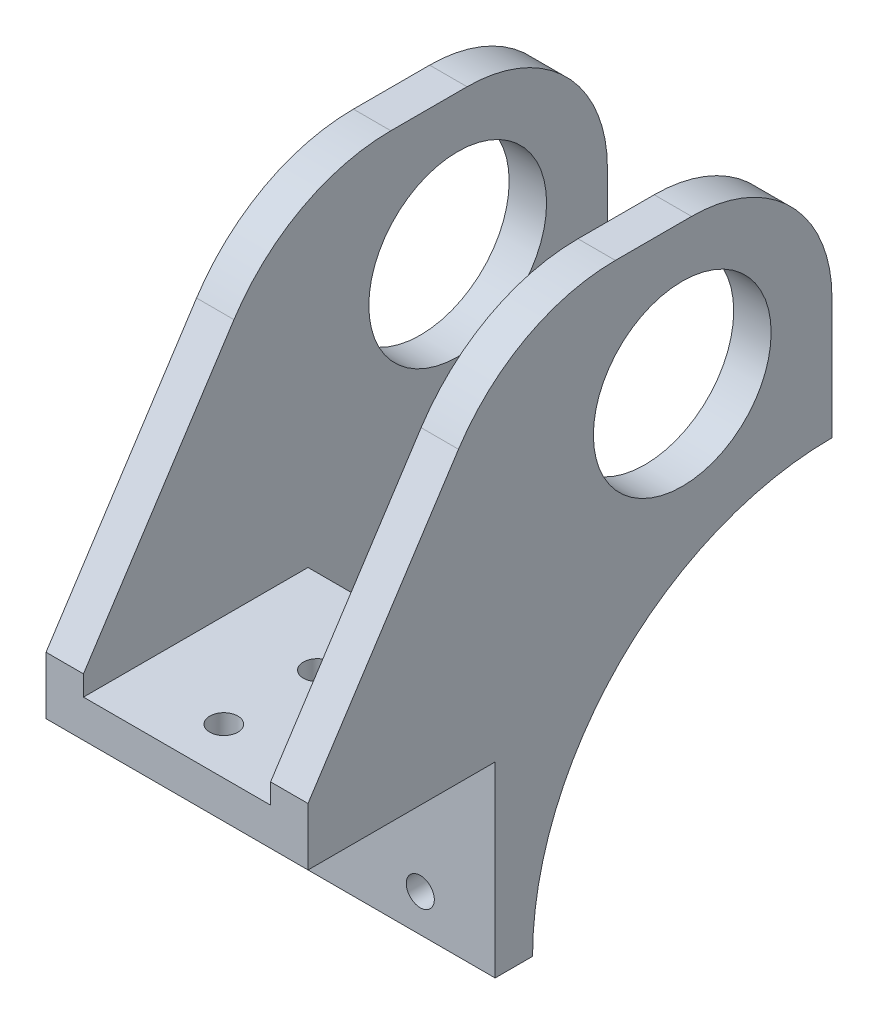
SolidWorks part; units mm, degrees
material "1060 合金"
ref_plane "前视基准面" through (0, 0, 0) normal (0, 0, 1) x (1, 0, 0)
ref_plane "上视基准面" through (0, 0, 0) normal (0, 1, 0) x (1, 0, 0)
ref_plane "右视基准面" through (0, 0, 0) normal (1, 0, 0) x (0, 0, -1)
sketch "草图1" plane through (0, 0, 0) normal (0, 0, 1) x (1, 0, 0)
  line L5 (30, -4) -> (30, 38)
  line L6 (30, 38) -> (34, 38)
  line L7 (34, 38) -> (34, 0)
  line L8 (34, 0) -> (46, 0)
  line L9 (46, 0) -> (46, 38)
  line L10 (46, 38) -> (50, 38)
  line L11 (50, 38) -> (50, -4)
  line L12 (50, -4) -> (30, -4)
  dimension "D1" = 4
  dimension "D2" = 4
  dimension "D3" = 42
  dimension "D6" = 12
  dimension "D7" = 4
extrude "凸台-拉伸1" add sketch "草图1" along normal mid plane 80
sketch "草图2" plane through (50, 0, 0) normal (1, 0, 0) x (0, 0, -1)
  line L0 (0, 38) -> (0, -4) construction
  line L1 (-40, 38) -> (40, 38) construction
  line L2 (-40, -4) -> (40, -4) construction
  circle A0 centre (22, 22) radius 9.5
  circle A1 centre (-22, 22) radius 9.5
  dimension "D1" = 19
  dimension "D2" = 16
  dimension "D3" = 22
extrude "切除-拉伸1" cut sketch "草图2" against normal through all
fillet "圆角1" radius 10 4 edges at (32, 38, 40) (48, 38, 40) (32, 38, -40) (48, 38, -40)
sketch "草图5" plane through (50, 0, 0) normal (1, 0, 0) x (0, 0, -1)
  line L0 (22, 22) -> (22, 37) construction
  line L1 (22, 22) -> (34.9904, 29.5) construction
  line L2 (0, -4) -> (0, 38) construction
  line L3 (-40, -4) -> (40, -4) construction
  line L4 (-30, 38) -> (30, 38) construction
  circle A0 centre (22, 22) radius 15 construction
  circle A2 centre (34.9904, 29.5) radius 1.5
  circle A3 centre (22, 7) radius 1.5
  circle A4 centre (9.0096, 29.5) radius 1.5
  circle A5 centre (-34.9904, 29.5) radius 1.5
  circle A6 centre (-22, 7) radius 1.5
  circle A7 centre (-9.0096, 29.5) radius 1.5
  point P12 (22, 22)
  dimension "D1" = 30
  dimension "D3" = 3
  dimension "D2" = 60
  dimension "D4" = 3
extrude "切除-拉伸4" cut sketch "草图5" against normal through all
sketch "草图6" plane through (30, 0, 0) normal (-1, 0, 0) x (0, 0, 1)
  circle A0 centre (-22, 22) radius 9.5 construction
  circle A1 centre (-22, 22) radius 9.5
  circle A2 centre (22, 22) radius 9.5 construction
  circle A3 centre (22, 22) radius 9.5
  circle A4 centre (-22, 22) radius 10.5
  circle A5 centre (22, 22) radius 10.5
  dimension "D1" = 1
extrude "切除-拉伸5" cut sketch "草图6" against normal blind 1.5
sketch "草图7" plane through (50, 0, 0) normal (1, 0, 0) x (0, 0, -1)
  line L0 (40, 28) -> (9.0096, 28) construction
  line L1 (9.0096, 28) -> (3.9996, 28) construction
  line L2 (3.9996, 28) -> (3.9996, 38) construction
  line L3 (-30, 38) -> (30, 38) construction
  line L5 (3.9996, 38) -> (-47.4626, 38)
  line L6 (3.9996, 38) -> (3.9996, -10.1754)
  line L7 (3.9996, -10.1754) -> (-47.4626, -10.1754)
  line L8 (-47.4626, 38) -> (-47.4626, -10.1754)
  circle A0 centre (9.0096, 29.5) radius 1.5 construction
  dimension "D1" = 48.1754
  dimension "D2" = 51.4622
extrude "切除-拉伸6" cut sketch "草图7" against normal blind 47
fillet "圆角2" radius 10 2 edges at (32, 38, -3.9996) (48, 38, -3.9996)
sketch "草图11" plane through (31.5, 0, 0) normal (-1, 0, 0) x (0, 0, 1)
  circle A1 centre (-22, 22) radius 11.25
  circle A2 centre (-22, 22) radius 11.5
  circle M3 centre (-22, 22) radius 10.5
extrude "凸台-拉伸3" add sketch "草图11" along normal blind 1.5 contours A1 M3
sketch "草图12" plane through (31.5, 0, 0) normal (-1, 0, 0) x (0, 0, 1)
  circle A0 centre (-22, 22) radius 10.5
  circle A1 centre (-22, 22) radius 11.25
extrude "凸台-拉伸4" add sketch "草图12" along normal blind 0.7
sketch "草图13" plane through (50, 0, 0) normal (1, 0, 0) x (0, 0, -1)
  circle A0 centre (22, 22) radius 10.5
  circle A1 centre (22, 22) radius 9.5
extrude "切除-拉伸8" cut sketch "草图13" against normal blind 1
sketch "草图15" plane through (31.5, 0, 0) normal (-1, 0, 0) x (0, 0, 1)
  circle A0 centre (-22, 22) radius 9.5
  circle A1 centre (-22, 22) radius 10.5
extrude "凸台-拉伸5" add sketch "草图15" along normal blind 0.5
sketch "草图17" plane through (0, 0, 0) normal (0, 1, 0) x (1, 0, 0)
  line L4 (34, 40) -> (34, 3.9996)
  line L5 (34, 3.9996) -> (46, 3.9996)
  line L6 (46, 3.9996) -> (46, 40)
  line L7 (46, 40) -> (34, 40)
  line L8 (34, 40) -> (34, 3.9996)
  line L10 (46, 3.9996) -> (46, 40)
  line L11 (46, 40) -> (34, 40)
  line L15 (34, 3.9996) -> (46, 3.9996)
  dimension "D1" = 0
extrude "凸台-拉伸6" add sketch "草图17" along normal blind 2
sketch "草图18" plane through (0, -4, 0) normal (0, -1, 0) x (1, 0, 0)
  line L4 (50, -40) -> (50, -3.9996)
  line L5 (50, -3.9996) -> (30, -3.9996)
  line L6 (30, -3.9996) -> (30, -40)
  line L7 (30, -40) -> (50, -40)
  line L8 (50, -40) -> (50, -3.9996)
  line L10 (30, -3.9996) -> (30, -40)
  line L11 (30, -40) -> (50, -40)
  line L15 (50, -3.9996) -> (30, -3.9996)
  dimension "D1" = 0
extrude "切除-拉伸9" cut sketch "草图18" against normal blind 2
sketch "草图19" plane through (50, 0, 0) normal (1, 0, 0) x (0, 0, -1)
  circle A0 centre (34.9904, 29.5) radius 1.5
  circle A1 centre (9.0096, 29.5) radius 1.5
  circle A2 centre (22, 7) radius 1.5
extrude "凸台-拉伸7" add sketch "草图19" against normal blind 4
sketch "草图20" plane through (30, 0, 0) normal (-1, 0, 0) x (0, 0, 1)
  circle A0 centre (-9.0096, 29.5) radius 1.5
  circle A1 centre (-22, 7) radius 1.5
  circle A2 centre (-34.9904, 29.5) radius 1.5
extrude "凸台-拉伸8" add sketch "草图20" against normal blind 4
sketch "草图21" plane through (30, 0, 0) normal (-1, 0, 0) x (0, 0, 1)
  line L1 (-3.9996, -2) -> (-40, -2) construction
  line L4 (-7.9998, -2) -> (-7.9998, 38)
  line L6 (-35.9998, -2) -> (-35.9998, 38)
  line L7 (-7.9998, 38) -> (-3.9996, 38)
  line L8 (-7.9998, 38) -> (-7.9998, -2)
  line L9 (-7.9998, -2) -> (-3.9996, -2)
  line L10 (-3.9996, 38) -> (-3.9996, -2)
  line L11 (-40, -2) -> (-35.9998, -2)
  line L12 (-40, -2) -> (-40, 38)
  line L13 (-40, 38) -> (-35.9998, 38)
  line L14 (-35.9998, -2) -> (-35.9998, 38)
  line M3 (-40, -2) -> (-3.9996, -2)
  line M4 (-3.9996, -2) -> (-3.9996, 28)
  arc M5 (-3.9996, 28) -> (-13.9996, 38) centre (-13.9996, 28) ccw
  arc M7 (-30, 38) -> (-40, 28) centre (-30, 28) ccw
  line M8 (-40, 28) -> (-40, -2)
  dimension "D1" = 40
  dimension "D2" = 28
  dimension "D3" = 40
  dimension "D4" = 4.0002
  dimension "D5" = 40
  dimension "D6" = 4.0002
extrude "凸台-拉伸9" add sketch "草图21" against normal blind 44 contours L6 M3 M7 M8 | L4 M3 M4 M5
sketch "草图22" plane through (50, 0, 0) normal (1, 0, 0) x (0, 0, -1)
  line L1 (-4.3042, -4.252) -> (60.1949, -4.252)
  line L2 (-4.3042, -4.252) -> (-4.3042, 45.5118)
  line L3 (-4.3042, 45.5118) -> (60.1949, 45.5118)
  line L4 (60.1949, -4.252) -> (60.1949, 45.5118)
  dimension "D1" = 49.7638
  dimension "D2" = 64.499
extrude "切除-拉伸10" cut sketch "草图22" along normal blind 38
sketch "草图23" plane through (0, 0, -3.9996) normal (0, 0, 1) x (1, 0, 0)
  line L0 (50, -2) -> (46, -2) construction
  line L1 (50, -2) -> (30, -2) construction
  line L2 (46, -2) -> (46, 2) construction
  line L4 (46, 2) -> (34, 2)
  line L5 (46, 2) -> (46, 36.0001)
  line L6 (46, 36.0001) -> (34, 36.0001)
  line L7 (34, 2) -> (34, 36.0001)
  dimension "D1" = 34.0001
  dimension "D2" = 12
extrude "切除-拉伸12" cut sketch "草图23" against normal blind 38
sketch "草图24" plane through (0, 0, -3.9996) normal (0, 0, 1) x (1, 0, 0)
  line L1 (30, -2) -> (53.9454, -2)
  line L2 (30, -2) -> (30, 46.4262)
  line L3 (30, 46.4262) -> (53.9454, 46.4262)
  line L4 (53.9454, -2) -> (53.9454, 46.4262)
  dimension "D1" = 48.4262
  dimension "D2" = 23.9454
extrude "切除-拉伸13" cut sketch "草图24" against normal blind 4
sketch "草图25" plane through (0, 0, -40) normal (0, 0, -1) x (-1, 0, 0)
  line L1 (-50, -2) -> (-30, -2)
  line L2 (-50, -2) -> (-50, 38)
  line L3 (-50, 38) -> (-30, 38)
  line L4 (-30, -2) -> (-30, 38)
  dimension "D1" = 40
  dimension "D2" = 20
extrude "切除-拉伸14" cut sketch "草图25" against normal blind 4
sketch "草图26" plane through (50, 0, 0) normal (1, 0, 0) x (0, 0, -1)
  line L1 (13.9996, 38) -> (7.9996, 38)
  line L4 (7.9996, 38) -> (7.9996, 36)
  line L5 (30, 38) -> (36, 38)
  line L8 (36, 38) -> (36, 36)
  arc A0 (36, 36) -> (30, 38) centre (30, 28) ccw
  arc A1 (13.9996, 38) -> (7.9996, 36) centre (13.9996, 28) ccw
  dimension "D2" = 6
  dimension "D4" = 6
extrude "凸台-拉伸10" add sketch "草图26" against normal blind 4
sketch "草图27" plane through (30, 0, 0) normal (-1, 0, 0) x (0, 0, 1)
  line L1 (-7.9996, 38) -> (-13.9996, 38)
  line L2 (-7.9996, 38) -> (-7.9996, 36)
  line L5 (-36, 38) -> (-30, 38)
  line L6 (-36, 38) -> (-36, 36)
  arc A0 (-7.9996, 36) -> (-13.9996, 38) centre (-13.9996, 28) ccw
  arc A1 (-30, 38) -> (-36, 36) centre (-30, 28) ccw
extrude "凸台-拉伸11" add sketch "草图27" against normal blind 4
sketch "草图30" plane through (50, 0, 0) normal (1, 0, 0) x (0, 0, -1)
  circle A0 centre (22, 22) radius 7.5
  circle A1 centre (22, 22) radius 10.5
extrude "凸台-拉伸12" add sketch "草图30" against normal blind 4
sketch "草图31" plane through (31, 0, 0) normal (-1, 0, 0) x (0, 0, 1)
  circle A1 centre (-22, 22) radius 9.5
  circle A2 centre (-22, 22) radius 10.5
extrude "凸台-拉伸13" add sketch "草图31" along normal blind 1
sketch "草图32" plane through (50, 0, 0) normal (1, 0, 0) x (0, 0, -1)
  circle A0 centre (22, 22) radius 7.5
  circle A1 centre (22, 22) radius 8.25
extrude "切除-拉伸15" cut sketch "草图32" against normal blind 0.8
sketch "草图34" plane through (0, -2, 0) normal (0, -1, 0) x (1, 0, 0)
  line L1 (30, -7.9996) -> (50, -7.9996)
  line L2 (30, -7.9996) -> (30, -11.9996)
  line L3 (30, -11.9996) -> (50, -11.9996)
  line L4 (50, -7.9996) -> (50, -11.9996)
  line L5 (50, -36) -> (50, -7.9996) construction
  line L7 (30, -36) -> (50, -36)
  line L8 (30, -36) -> (30, -32)
  line L9 (30, -32) -> (50, -32)
  line L10 (50, -36) -> (50, -32)
  dimension "D1" = 4
  dimension "D2" = 20
  dimension "D3" = 4
  dimension "D4" = 20
extrude "凸台-拉伸14" add sketch "草图34" along normal blind 20
sketch "草图37" plane through (50, 0, 0) normal (1, 0, 0) x (0, 0, -1)
  circle A0 centre (22, 22) radius 9.5
extrude "切除-拉伸19" cut sketch "草图37" against normal blind 10
sketch "草图38" plane through (50, 0, 0) normal (1, 0, 0) x (0, 0, -1)
  circle A0 centre (22, 22) radius 10.5
extrude "切除-拉伸20" cut sketch "草图38" against normal blind 1
sketch "草图39" plane through (0, 0, -36) normal (0, 0, -1) x (-1, 0, 0)
  line L0 (-30, -22) -> (-30, 38) construction
  line L1 (-50, 38) -> (-46, 38)
  line L2 (-50, 38) -> (-50, 2)
  line L3 (-50, 2) -> (-46, 2)
  line L4 (-46, 38) -> (-46, 2)
  line L5 (-34, 38) -> (-30, 38)
  line L6 (-34, 38) -> (-34, 2)
  line L7 (-34, 2) -> (-30, 2)
  line L8 (-30, 38) -> (-30, 2)
extrude "凸台-拉伸15" add sketch "草图39" along normal blind 22
sketch "草图40" plane through (30, 0, 0) normal (-1, 0, 0) x (0, 0, 1)
  line L0 (-22, 22) -> (-44, 22) construction
  circle A0 centre (-44, 22) radius 9.5
  dimension "D2" = 19
  dimension "D1" = 22
extrude "切除-拉伸21" cut sketch "草图40" against normal blind 22
sketch "草图41" plane through (30, 0, 0) normal (-1, 0, 0) x (0, 0, 1)
  circle A0 centre (-22, 22) radius 9.5
extrude "凸台-拉伸16" add sketch "草图41" against normal blind 4
sketch "草图44" plane through (50, 0, 0) normal (1, 0, 0) x (0, 0, -1)
  circle A0 centre (22, 22) radius 10.5
extrude "凸台-拉伸17" add sketch "草图44" against normal blind 4
sketch "草图45" plane through (30, 0, 0) normal (-1, 0, 0) x (0, 0, 1)
  line L10 (-7.9996, 38) -> (-58, 38)
  line L11 (-58, 38) -> (-58, 2)
  line L12 (-58, 2) -> (-36, 2)
  line L13 (-36, 2) -> (-36, -22)
  line L14 (-36, -22) -> (-32, -22)
  line L15 (-32, -22) -> (-32, -2)
  line L16 (-32, -2) -> (-11.9996, -2)
  line L17 (-11.9996, -2) -> (-11.9996, -22)
  line L18 (-11.9996, -22) -> (-7.9996, -22)
  line L19 (-7.9996, -22) -> (-7.9996, 38)
  line L20 (-7.9996, 38) -> (-58, 38)
  line L21 (-58, 38) -> (-58, 2)
  line L22 (-58, 2) -> (-36, 2)
  line L23 (-36, 2) -> (-36, -22)
  line L24 (-36, -22) -> (-32, -22)
  line L25 (-32, -22) -> (-32, -2)
  line L26 (-32, -2) -> (-11.9996, -2)
  line L27 (-11.9996, -2) -> (-11.9996, -22)
  line L28 (-11.9996, -22) -> (-7.9996, -22)
  line L29 (-7.9996, -22) -> (-7.9996, 38)
  circle A0 centre (-44, 22) radius 9.5
  dimension "D1" = 0
extrude "凸台-拉伸18" add sketch "草图45" along normal blind 8
sketch "草图46" plane through (34, 0, 0) normal (1, 0, 0) x (0, 0, -1)
  line L5 (7.9996, 2) -> (36, 2)
  line L6 (36, 2) -> (58, 2)
  line L7 (58, 2) -> (58, 38)
  line L8 (58, 38) -> (7.9996, 38)
  line L9 (7.9996, 38) -> (7.9996, 2)
  line L10 (7.9996, 2) -> (36, 2)
  line L11 (36, 2) -> (58, 2)
  line L12 (58, 2) -> (58, 38)
  line L13 (58, 38) -> (7.9996, 38)
  line L14 (7.9996, 38) -> (7.9996, 2)
  dimension "D1" = 0
extrude "切除-拉伸22" cut sketch "草图46" against normal blind 8
sketch "草图50" plane through (0, 0, -58) normal (0, 0, -1) x (-1, 0, 0)
  line L4 (-50, 38) -> (-50, 2)
  line L5 (-50, 2) -> (-46, 2)
  line L6 (-46, 2) -> (-46, 38)
  line L7 (-46, 38) -> (-50, 38)
  line L8 (-50, 38) -> (-50, 2)
  line L9 (-50, 2) -> (-46, 2)
  line L10 (-46, 2) -> (-46, 38)
  line L11 (-46, 38) -> (-50, 38)
  line L12 (-22, 38) -> (-26, 38)
  line L13 (-26, 38) -> (-26, 2)
  line L14 (-26, 2) -> (-22, 2)
  line L15 (-22, 2) -> (-22, 38)
  line L16 (-22, 38) -> (-26, 38)
  line L17 (-26, 38) -> (-26, 2)
  line L18 (-26, 2) -> (-22, 2)
  line L19 (-22, 2) -> (-22, 38)
  dimension "D1" = 0
  dimension "D2" = 0
extrude "凸台-拉伸19" add sketch "草图50" along normal blind 2
sketch "草图51" plane through (22, 0, 0) normal (-1, 0, 0) x (0, 0, 1)
  line L0 (-60, 2) -> (-36, 2)
  line L1 (-36, 2) -> (-36, -22) construction
  line L2 (-36, 2) -> (-36, -22)
  arc A1 (-36, -22) -> (-60, 2) centre (-60, -22) ccw
extrude "凸台-拉伸20" add sketch "草图51" against normal blind 4
sketch "草图54" plane through (50, 0, 0) normal (1, 0, 0) x (0, 0, -1)
  line L0 (36, 2) -> (36, -22) construction
  line L1 (60, 2) -> (36, 2) construction
  line L2 (36, 2) -> (36, -22)
  line L3 (60, 2) -> (36, 2)
  arc A0 (60, 2) -> (36, -22) centre (60, -22) ccw construction
  arc A1 (60, 2) -> (36, -22) centre (60, -22) ccw
extrude "凸台-拉伸21" add sketch "草图54" against normal blind 4
sketch "草图55" plane through (0, 0, -7.9996) normal (0, 0, 1) x (1, 0, 0)
  line L0 (36, -22) -> (36, -12) construction
  line L1 (50, -22) -> (22, -22) construction
  line L3 (30, -18) -> (42, -18) construction
  line L4 (30, -18) -> (30, -6) construction
  line L5 (30, -6) -> (42, -6) construction
  line L6 (42, -18) -> (42, -6) construction
  line L7 (30, -18) -> (42, -6) construction
  line L8 (30, -6) -> (42, -18) construction
  circle A0 centre (30, -6) radius 1.5
  circle A1 centre (42, -6) radius 1.5
  circle A2 centre (42, -18) radius 1.5
  circle A3 centre (30, -18) radius 1.5
  point P18 (36, -12)
  dimension "D3" = 3
  dimension "D1" = 10
  dimension "D2" = 12
  dimension "D4" = 4
extrude "切除-拉伸23" cut sketch "草图55" against normal blind 30
sketch "草图57" plane through (22, 0, 0) normal (-1, 0, 0) x (0, 0, 1)
  line L0 (-11.9996, -2) -> (-7.9996, -2) construction
  line L1 (-7.9996, -22) -> (-7.9996, 38) construction
  line L2 (-7.9996, -2) -> (-33.9998, 38)
  line L3 (-7.9996, 38) -> (-60, 38) construction
  line L4 (-33.9998, 38) -> (-7.9996, 38)
  line L5 (-7.9996, 38) -> (-7.9996, -2)
extrude "切除-拉伸24" cut sketch "草图57" against normal blind 30
fillet "圆角4" radius 20 2 edges at (24, 38, -33.9998) (48, 38, -33.9998)
sketch "草图58" plane through (0, 0, -11.9996) normal (0, 0, -1) x (-1, 0, 0)
  line L4 (-22, -2) -> (-50, -2)
  line L5 (-50, -2) -> (-50, -22)
  line L6 (-50, -22) -> (-22, -22)
  line L7 (-22, -22) -> (-22, -2)
  line L8 (-22, -2) -> (-50, -2)
  line L9 (-50, -2) -> (-50, -22)
  line L10 (-50, -22) -> (-22, -22)
  line L11 (-22, -22) -> (-22, -2)
  dimension "D1" = 0
extrude "切除-拉伸25" cut sketch "草图58" against normal blind 10
sketch "草图59" plane through (0, -2, 0) normal (0, -1, 0) x (1, 0, 0)
  line L0 (50, -32) -> (50, -7.9996) construction
  line L1 (22, -7.9996) -> (50, -7.9996)
  line L2 (22, -7.9996) -> (22, -11.9996)
  line L3 (22, -11.9996) -> (50, -11.9996)
  line L4 (50, -7.9996) -> (50, -11.9996)
  dimension "D1" = 4
extrude "切除-拉伸26" cut sketch "草图59" against normal blind 10
sketch "草图60" plane through (0, -2, 0) normal (0, -1, 0) x (1, 0, 0)
  line L0 (36, -11.9996) -> (36, -16.9996) construction
  line L1 (22, -11.9996) -> (50, -11.9996) construction
  line L2 (36, -16.9996) -> (36, -26.9996) construction
  circle A0 centre (36, -16.9996) radius 1.5
  circle A1 centre (36, -26.9996) radius 1.5
  dimension "D3" = 3
  dimension "D4" = 3
  dimension "D1" = 5
  dimension "D2" = 10
extrude "切除-拉伸27" cut sketch "草图60" against normal blind 10
sketch "草图61" plane through (22, 0, 0) normal (-1, 0, 0) x (0, 0, 1)
  circle A0 centre (-44, 22) radius 9.5 construction
  circle A1 centre (-44, 22) radius 9.5
extrude "凸台-拉伸22" add sketch "草图61" against normal up to surface (4 mm away) up to face at (26, 12.5191, -35.3515)
sketch "草图62" plane through (50, 0, 0) normal (1, 0, 0) x (0, 0, -1)
  circle A0 centre (44, 22) radius 9.5 construction
  circle A1 centre (44, 22) radius 9.5
extrude "凸台-拉伸23" add sketch "草图62" against normal up to surface (4 mm away) up to face at (46, 22, -53.5)
sketch "草图64" plane through (0, 0, -60) normal (0, 0, -1) x (-1, 0, 0)
  line L4 (-22, 2) -> (-22, 38)
  line L5 (-22, 38) -> (-26, 38)
  line L6 (-26, 38) -> (-26, 2)
  line L7 (-26, 2) -> (-22, 2)
  line L8 (-22, 2) -> (-22, 38)
  line L9 (-22, 38) -> (-26, 38)
  line L10 (-26, 38) -> (-26, 2)
  line L11 (-26, 2) -> (-22, 2)
  line L12 (-46, 38) -> (-50, 38)
  line L13 (-50, 38) -> (-50, 2)
  line L14 (-50, 2) -> (-46, 2)
  line L15 (-46, 2) -> (-46, 38)
  line L16 (-46, 38) -> (-50, 38)
  line L17 (-50, 38) -> (-50, 2)
  line L18 (-50, 2) -> (-46, 2)
  line L19 (-46, 2) -> (-46, 38)
  dimension "D1" = 0
  dimension "D2" = 0
extrude "凸台-拉伸24" add sketch "草图64" along normal blind 8
sketch "草图65" plane through (50, 0, 0) normal (1, 0, 0) x (0, 0, -1)
  line L0 (36, -22) -> (36, 10) construction
  line L1 (36, 10) -> (68, 10) construction
  line L2 (68, 38) -> (68, 2) construction
  line L3 (68, 10) -> (36, -22) construction
  line L4 (36, -22) -> (68, -22) construction
  circle A0 centre (68, -22) radius 32
extrude "切除-拉伸28" cut sketch "草图65" against normal blind 39
sketch "草图66" plane through (50, 0, 0) normal (1, 0, 0) x (0, 0, -1)
  line L0 (11.9996, -2) -> (51.9996, -2) construction
  line L1 (51.9996, -2) -> (51.9996, 23) construction
  circle A0 centre (51.9996, 23) radius 9.5
  dimension "D3" = 19
  dimension "D1" = 40
  dimension "D2" = 25
extrude "切除-拉伸29" cut sketch "草图66" against normal blind 41
fillet "圆角5" radius 15 2 edges at (48, 38, -68) (24, 38, -68)
